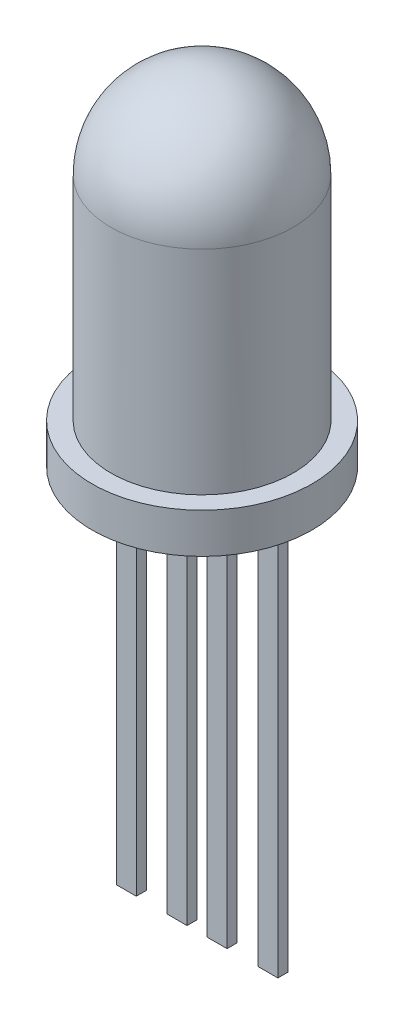
SolidWorks part; units mm, degrees
ref_plane "Alzado" through (0, 0, 0) normal (0, 0, 1) x (1, 0, 0)
ref_plane "Planta" through (0, 0, 0) normal (0, 1, 0) x (1, 0, 0)
ref_plane "Vista lateral" through (0, 0, 0) normal (1, 0, 0) x (0, 0, -1)
sketch "Croquis1" plane through (0, 0, 0) normal (0, 0, 1) x (1, 0, 0)
  line L0 (0, -55.2734) -> (0, 62.6926) construction
  line L1 (0, 0) -> (-2.75, 0)
  line L2 (-2.75, 0) -> (-2.75, 1)
  line L3 (-2.75, 1) -> (-2.28, 1)
  line L4 (-2.28, 1) -> (-2.28, 6.32)
  line L5 (0, 8.6) -> (0, 0)
  line L6 (0, 8.6) -> (-11.2359, 8.6) construction
  arc A0 (-2.28, 6.32) -> (0, 8.6) centre (0, 6.32) cw
  dimension "D1" = 2.28
  dimension "D2" = 8.6
  dimension "D3" = 2.75
  dimension "D4" = 7.6
revolve "Revolución1" add sketch "Croquis1" angle 360 about L0
sketch "Croquis3" plane through (0, 0, 0) normal (0, -1, 0) x (1, 0, 0)
  line L0 (0, 0) -> (-2.0062, 0) construction
  line L1 (0, 0) -> (0, 1.9606) construction
  line L2 (1.52, 0.125) -> (2.02, -0.125) construction
  line L3 (-0.25, -0.125) -> (-0.75, -0.125)
  line L4 (-0.25, -0.125) -> (-0.25, 0.125)
  line L5 (-0.25, 0.125) -> (-0.75, 0.125)
  line L6 (-0.75, -0.125) -> (-0.75, 0.125)
  line L7 (-0.25, -0.125) -> (-0.75, 0.125) construction
  line L8 (-0.25, 0.125) -> (-0.75, -0.125) construction
  line L9 (-1.52, -0.125) -> (-2.02, -0.125)
  line L10 (-1.52, -0.125) -> (-1.52, 0.125)
  line L11 (-1.52, 0.125) -> (-2.02, 0.125)
  line L12 (-2.02, -0.125) -> (-2.02, 0.125)
  line L13 (-1.52, -0.125) -> (-2.02, 0.125) construction
  line L14 (-1.52, 0.125) -> (-2.02, -0.125) construction
  line L15 (1.52, -0.125) -> (2.02, 0.125) construction
  line L16 (0.25, 0.125) -> (0.75, -0.125) construction
  line L17 (0.25, -0.125) -> (0.75, 0.125) construction
  line L18 (2.02, -0.125) -> (2.02, 0.125)
  line L19 (1.52, 0.125) -> (2.02, 0.125)
  line L20 (1.52, -0.125) -> (1.52, 0.125)
  line L21 (1.52, -0.125) -> (2.02, -0.125)
  line L22 (0.75, -0.125) -> (0.75, 0.125)
  line L23 (0.25, 0.125) -> (0.75, 0.125)
  line L24 (0.25, -0.125) -> (0.25, 0.125)
  line L25 (0.25, -0.125) -> (0.75, -0.125)
  point P4 (-0.5, 0)
  point P11 (-1.77, 0)
  point P25 (1.77, 0)
  point P26 (0.5, 0)
  dimension "D1" = 0.5
  dimension "D2" = 0.5
  dimension "D3" = 0.25
  dimension "D4" = 1.27
extrude "Saliente-Extruir1" add sketch "Croquis3" along normal blind 10
